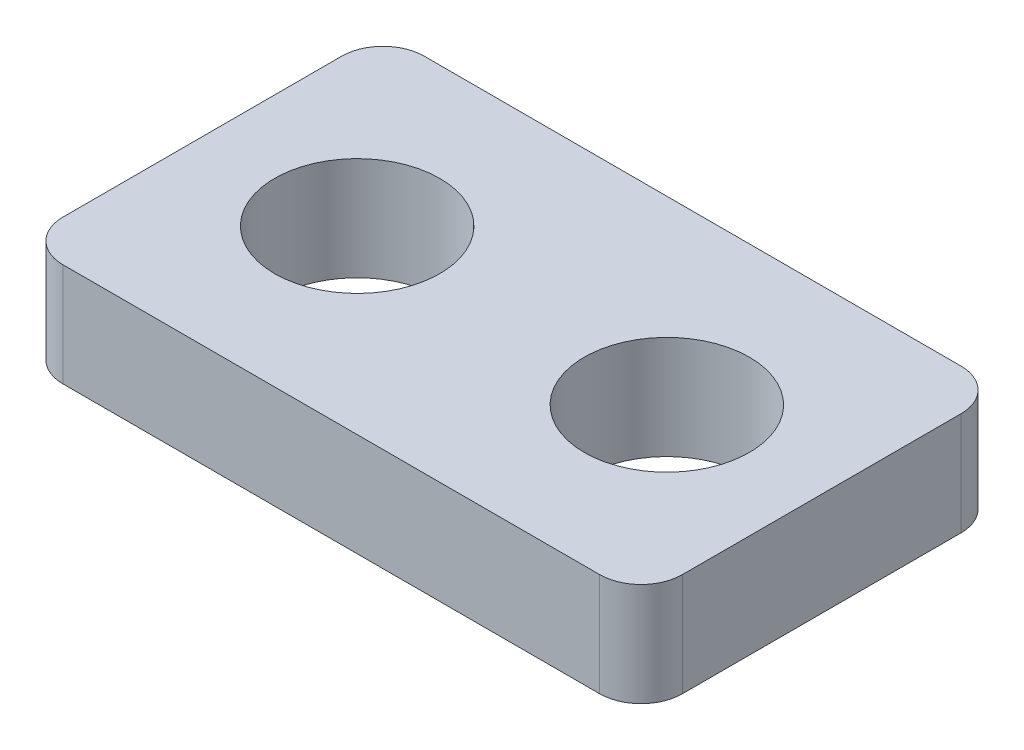
SolidWorks part; units mm, degrees
ref_plane "Front Plane" through (0, 0, 0) normal (0, 0, 1) x (1, 0, 0)
ref_plane "Top Plane" through (0, 0, 0) normal (0, 1, 0) x (1, 0, 0)
ref_plane "Right Plane" through (0, 0, 0) normal (1, 0, 0) x (0, 0, -1)
sketch "Sketch1" plane through (0, 0, 0) normal (0, 1, 0) x (1, 0, 0)
  line L1 (-6, -3.5) -> (6, -3.5)
  line L2 (-6, -3.5) -> (-6, 3.5)
  line L3 (-6, 3.5) -> (6, 3.5)
  line L4 (6, -3.5) -> (6, 3.5)
  line L5 (-6, -3.5) -> (6, 3.5) construction
  line L6 (-6, 3.5) -> (6, -3.5) construction
  point P0 (0, 0)
  dimension "D1" = 12
  dimension "D2" = 7
extrude "Boss-Extrude1" add sketch "Sketch1" along normal blind 2
sketch "Sketch2" plane through (0, 2, 0) normal (0, 1, 0) x (1, 0, 0)
  line L0 (0, 0) -> (-3, 0) construction
  line L1 (0, 0) -> (3, 0) construction
  circle A0 centre (-3, 0) radius 1.6
  circle A1 centre (3, 0) radius 1.6
  dimension "D1" = 3.2
  dimension "D2" = 3
extrude "Cut-Extrude1" cut sketch "Sketch2" against normal through all
fillet "Fillet1" radius 0.8 4 edges at (-6, 1, 3.5) (-6, 1, -3.5) (6, 1, -3.5) (6, 1, 3.5)
